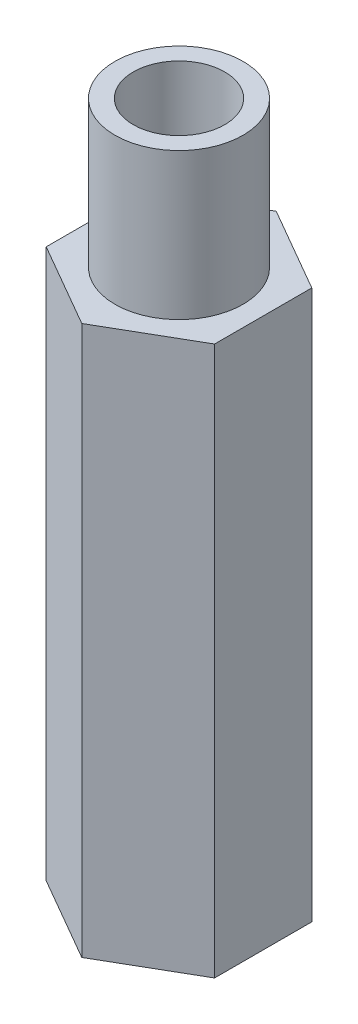
SolidWorks part; units mm, degrees
ref_plane "前视基准面" through (0, 0, 0) normal (0, 0, 1) x (1, 0, 0)
ref_plane "上视基准面" through (0, 0, 0) normal (0, 1, 0) x (1, 0, 0)
ref_plane "右视基准面" through (0, 0, 0) normal (1, 0, 0) x (0, 0, -1)
other "Configuration Table"
sketch "草图1" plane through (0, 0, 0) normal (0, 1, 0) x (1, 0, 0)
  line L1 (0, 2.6558) -> (-2.3, 1.3279)
  line L2 (-2.3, 1.3279) -> (-2.3, -1.3279)
  line L3 (-2.3, -1.3279) -> (0, -2.6558)
  line L4 (0, -2.6558) -> (2.3, -1.3279)
  line L5 (2.3, -1.3279) -> (2.3, 1.3279)
  line L6 (2.3, 1.3279) -> (0, 2.6558)
  circle A0 centre (0, 0) radius 2.3 construction
  dimension "D1" = 4.6
extrude "凸台-拉伸1" add sketch "草图1" along normal blind 15
sketch "草图2" plane through (0, 15, 0) normal (0, 1, 0) x (1, 0, 0)
  circle A0 centre (0, 0) radius 1.75
  dimension "D1" = 3.5
extrude "凸台-拉伸2" add sketch "草图2" along normal blind 4
cosmetic thread "装饰螺纹线1" parameters "D2"=3
hole_wizard "M3 螺纹孔1" positions "草图3" profile "草图4" tap size "M3" standard "GB" end condition through all
sketch "草图3" plane through (0, 19, 0) normal (0, 1, 0) x (1, 0, 0)
  point P0 (0, 0)
sketch "草图4" plane through (0, 19, 0) normal (1, 0, 0) x (0, 0, 1)
  line L0 (0, 0) -> (0, 19)
  line L1 (0, 19) -> (1.25, 19)
  line L2 (1.25, 19) -> (1.25, 0)
  line L5 (1.25, 0) -> (0, 0)
  line L11 (0, -6.35) -> (0, 107.95) construction
  dimension "通孔螺纹孔钻头直径" = 2.5
  dimension "通孔螺纹孔钻头深度" = 19
cosmetic thread "孔螺蚊线1" parameters "D2"=3
